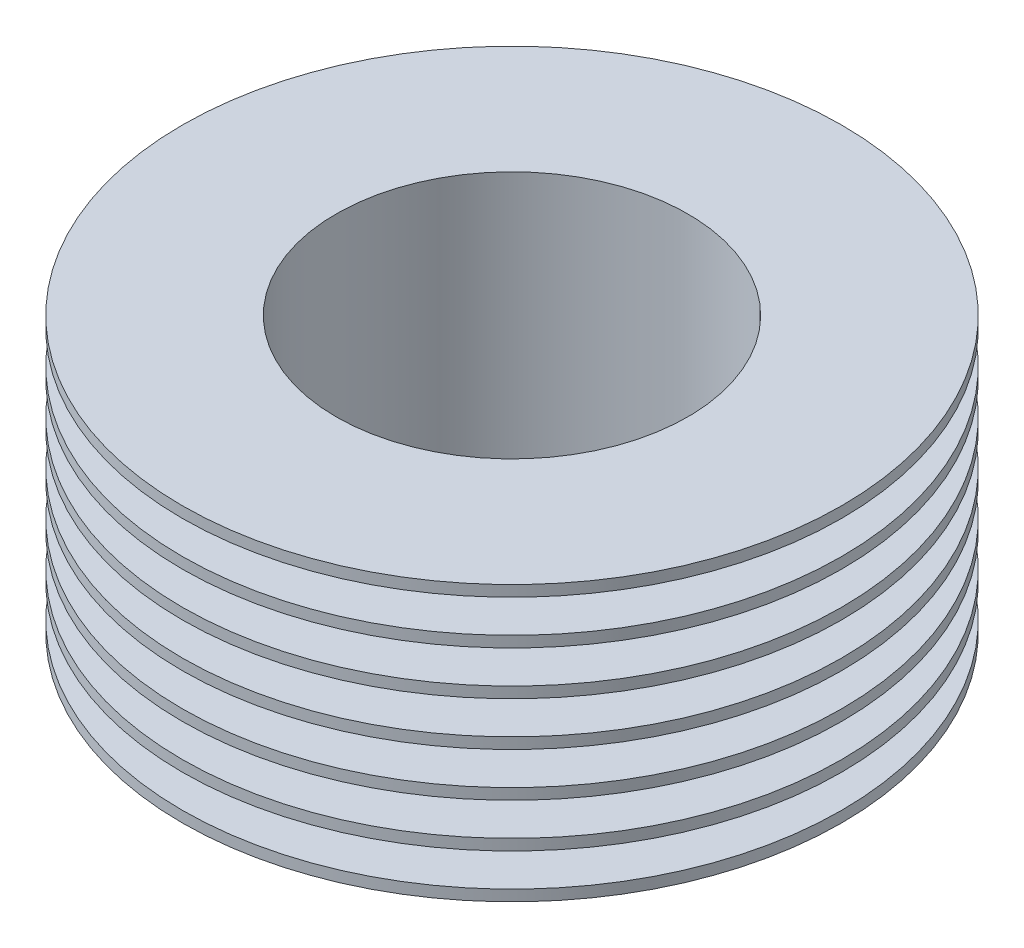
SolidWorks part; units mm, degrees
ref_plane "Front Plane" through (0, 0, 0) normal (0, 0, 1) x (1, 0, 0)
ref_plane "Top Plane" through (0, 0, 0) normal (0, 1, 0) x (1, 0, 0)
ref_plane "Right Plane" through (0, 0, 0) normal (1, 0, 0) x (0, 0, -1)
sketch "Sketch1" plane through (0, 0, 0) normal (1, 0, 0) x (0, 0, -1)
  line L0 (0, 28.0586) -> (0, -24.3494) construction
  line L4 (-18, 13.8387) -> (-18, 9.8387)
  line L5 (-18, 9.8387) -> (-30, 9.8387)
  line L6 (-30, 9.8387) -> (-30, 8.8387)
  line L7 (-30, 8.8387) -> (-16, 8.8387)
  line L8 (-16, 8.8387) -> (-16, 13.8387)
  line L11 (-18, 13.8387) -> (-16, 13.8387)
  dimension "D1" = 5
  dimension "D2" = 32
  dimension "D4" = 36
  dimension "D5" = 1
  dimension "D7" = 60
revolve "Revolve1" add sketch "Sketch1" angle 360 about L0
pattern_linear "LPattern1" count 7 spacing 4 along (0, 1, 0) of "Revolve1"
sketch "Sketch3" plane through (0, 37.8387, 0) normal (0, 1, 0) x (1, 0, 0)
  circle A0 centre (0, 0) radius 19.0474
extrude "Cut-Extrude3" cut sketch "Sketch3" against normal up to surface (4 mm away) up to face at (0, 33.8387, 30)
